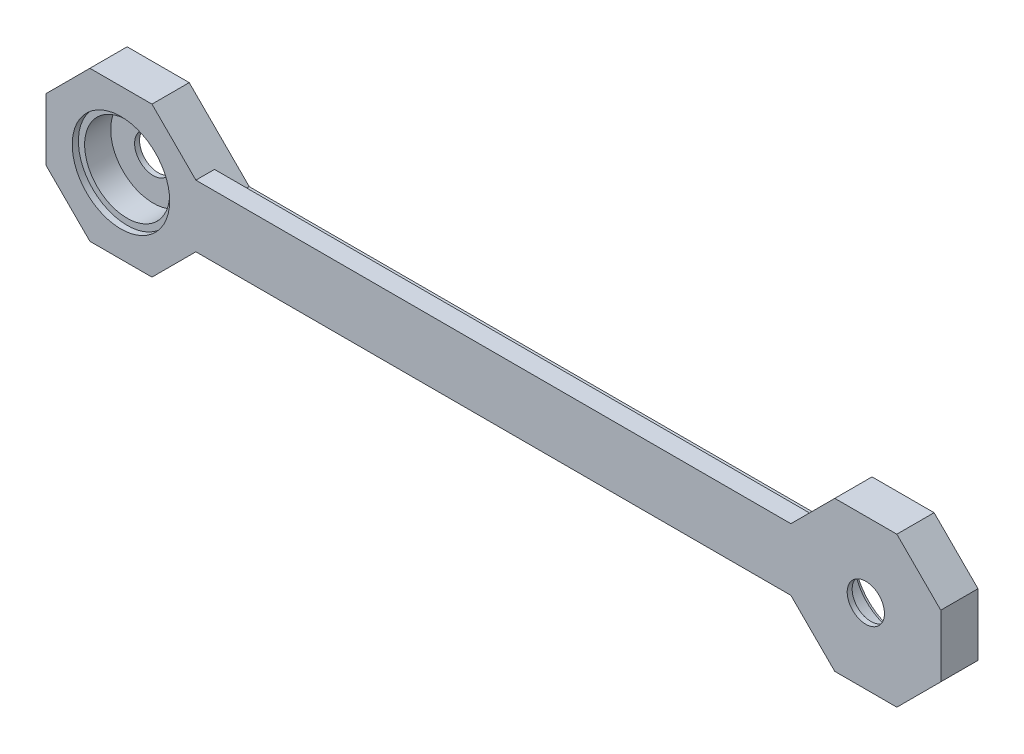
SolidWorks part; units mm, degrees
material "AISI 1020"
ref_plane "Front Plane" through (0, 0, 0) normal (0, 0, 1) x (1, 0, 0)
ref_plane "Top Plane" through (0, 0, 0) normal (0, 1, 0) x (1, 0, 0)
ref_plane "Right Plane" through (0, 0, 0) normal (1, 0, 0) x (0, 0, -1)
sketch "Sketch1" plane through (0, 0, 0) normal (0, 0, 1) x (1, 0, 0)
  line L0 (-120, 0) -> (0, 0) construction
  line L17 (5, 12.0711) -> (-5, 12.0711)
  line L18 (-5, 12.0711) -> (-12.0711, 5)
  line L20 (-12.0711, -5) -> (-5, -12.0711)
  line L21 (-5, -12.0711) -> (5, -12.0711)
  line L22 (5, -12.0711) -> (12.0711, -5)
  line L23 (12.0711, -5) -> (12.0711, 5)
  line L24 (12.0711, 5) -> (5, 12.0711)
  line L25 (-125, 12.0711) -> (-132.0711, 5)
  line L26 (-132.0711, 5) -> (-132.0711, -5)
  line L27 (-132.0711, -5) -> (-125, -12.0711)
  line L28 (-125, -12.0711) -> (-115, -12.0711)
  line L29 (-115, -12.0711) -> (-107.9289, -5)
  line L31 (-107.9289, 5) -> (-115, 12.0711)
  line L32 (-115, 12.0711) -> (-125, 12.0711)
  line L33 (-107.9289, 5) -> (-12.0711, 5)
  line L34 (-107.9289, -5) -> (-12.0711, -5)
  line L35 (-115, 12.0711) -> (-105.3236, 2.3947)
  line L36 (-115, -12.0711) -> (-105.3236, -2.3947)
  line L37 (-5, 12.0711) -> (-14.6764, 2.3947)
  line L38 (-14.6764, -2.3947) -> (-5, -12.0711)
  line L39 (-105.3236, 2.3947) -> (-14.6764, 2.3947)
  line L40 (-105.3236, -2.3947) -> (-14.6764, -2.3947)
  line L42 (-107.9289, -5) -> (-107.9289, 0) [skipped]
  line L43 (-12.0711, 0) -> (-12.0711, -5) [skipped]
  arc A0 (-8.5355, -8.5355) -> (-8.5355, 8.5355) centre (0, 0) ccw construction
  arc A1 (-111.4645, 8.5355) -> (-111.4645, -8.5355) centre (-120, 0) ccw construction
  circle A2 centre (-120, 0) radius 3
  circle A3 centre (0, 0) radius 3
  dimension "D1" = 10
  dimension "D2" = 10
  dimension "D3" = 120
extrude "Boss-Extrude1" add sketch "Sketch1" against normal blind 6 contours L36 L40 L38 L20 L21 L22 L23 L24 L17 L18 L37 L39 L35 L31 L32 L25 L26 L27 L28 L29 A3 A2
sketch "Sketch2" plane through (0, 0, 0) normal (0, 0, 1) x (1, 0, 0)
  line L0 (-107.9289, 5) -> (-12.0711, 5)
  line L1 (-105.3236, 2.3947) -> (-107.9289, 5)
  line L2 (-115, 12.0711) -> (-105.3236, 2.3947) construction
  line L3 (-120, 0) -> (0, 0) construction
  line L4 (-107.9289, -5) -> (-12.0711, -5)
  line L5 (-14.6764, 2.3947) -> (-12.0711, 5)
  line L6 (-5, 12.0711) -> (-14.6764, 2.3947) construction
  line L7 (-14.6764, 2.3947) -> (-105.3236, 2.3947)
  line L8 (-14.6764, -2.3947) -> (-12.0711, -5)
  line L9 (-105.3236, -2.3947) -> (-107.9289, -5)
  line L10 (-14.6764, -2.3947) -> (-105.3236, -2.3947)
  line L11 (-107.9289, -5) -> (-12.0711, -5)
  dimension "D1" = 10
extrude "Boss-Extrude2" add sketch "Sketch2" against normal blind 3 contours L8 L10 L9 L4 | L7 L5 L0 L1
sketch "Sketch3" plane through (0, 0, -6) normal (0, 0, -1) x (-1, 0, 0)
  circle A0 centre (0, 0) radius 6.85
extrude "Cut-Extrude1" cut sketch "Sketch3" against normal blind 5.2 contours A0
sketch "Sketch4" plane through (0, 0, -6) normal (0, 0, -1) x (-1, 0, 0)
  circle A0 centre (0, 0) radius 7.85
extrude "Cut-Extrude2" cut sketch "Sketch4" against normal blind 1
sketch "Sketch5" plane through (0, 0, 0) normal (0, 0, 1) x (1, 0, 0)
  circle A0 centre (-120, 0) radius 6.85
extrude "Cut-Extrude3" cut sketch "Sketch5" against normal blind 5.2
sketch "Sketch6" plane through (0, 0, 0) normal (0, 0, 1) x (1, 0, 0)
  circle A0 centre (-120, 0) radius 7.85
extrude "Cut-Extrude4" cut sketch "Sketch6" against normal blind 1
equation "\"A\"= 100"
equation "\"B\"= 100"
equation "\"C\"= 100"
equation "\"D\"= 100"
equation "\"E\"= 100"
